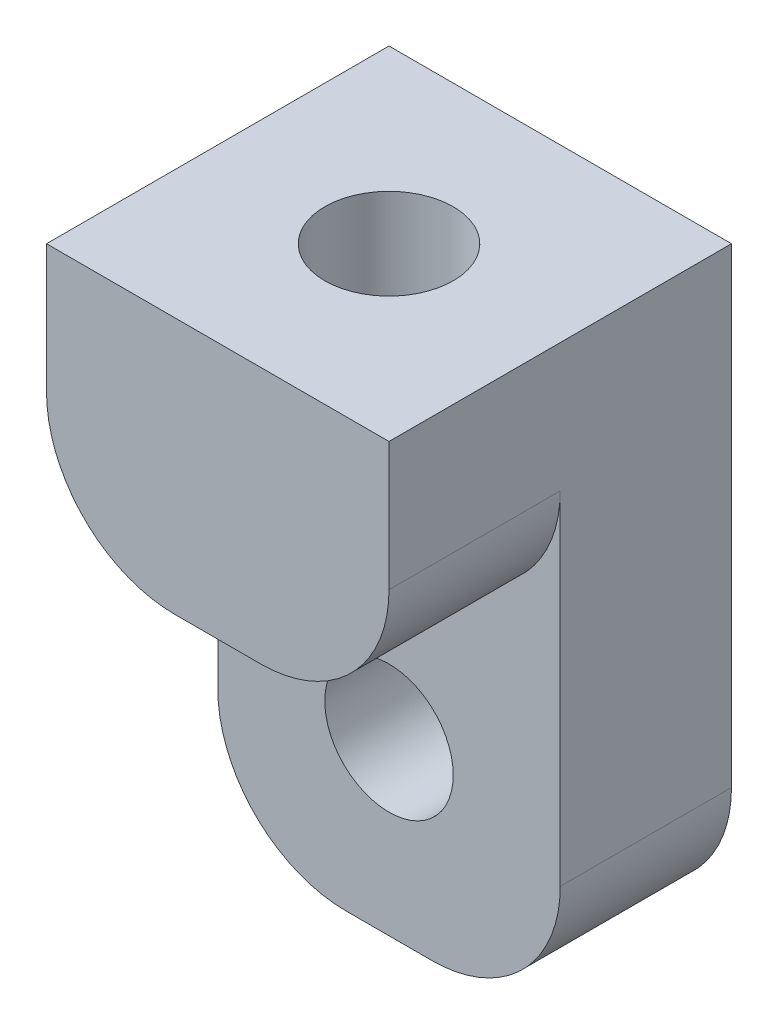
SolidWorks part; units mm, degrees
material "ABS"
ref_plane "Front Plane" through (0, 0, 0) normal (0, 0, 1) x (1, 0, 0)
ref_plane "Top Plane" through (0, 0, 0) normal (0, 1, 0) x (1, 0, 0)
ref_plane "Right Plane" through (0, 0, 0) normal (1, 0, 0) x (0, 0, -1)
sketch "Sketch1" plane through (0, 0, 0) normal (0, 0, 1) x (1, 0, 0)
  line L1 (-20, 50) -> (20, 50)
  line L2 (-20, 50) -> (-20, -20)
  line L3 (-20, -20) -> (20, -20)
  line L4 (20, 50) -> (20, -20)
  circle A0 centre (0, 0) radius 7.5
  point P6 (0, 0)
  point P8 (30.9278, -35.0258)
  point P9 (0, -20)
  point P10 (-25.8247, 54.201)
  dimension "D1" = 15
  dimension "D2" = 20
  dimension "D3" = 70
  dimension "D4" = 40
extrude "Boss-Extrude1" add sketch "Sketch1" along normal blind 40 contours L2 L3 L4 L1
sketch "Sketch2" plane through (0, 50, 0) normal (0, 1, 0) x (1, 0, 0)
  line L0 (-20, 0) -> (20, -40) construction
  line L4 (20, 0) -> (-20, 0)
  line L5 (-20, 0) -> (-20, -40)
  line L6 (-20, -40) -> (20, -40)
  line L7 (20, -40) -> (20, 0)
  line L8 (20, 0) -> (-20, 0)
  line L9 (-20, 0) -> (-20, -40)
  line L10 (-20, -40) -> (20, -40)
  line L11 (20, -40) -> (20, 0)
  circle A0 centre (0, -20) radius 7.5
  point P6 (0, -20)
  dimension "D2" = 15
  dimension "D1" = 0
extrude "Cut-Extrude1" cut sketch "Sketch2" against normal blind 20 contours L0 A0 | A0 L0
sketch "Sketch3" plane through (0, 0, 40) normal (0, 0, 1) x (1, 0, 0)
  line L0 (20, -20) -> (20, 50) construction
  line L1 (-20, -20) -> (20, -20)
  line L2 (-20, -20) -> (-20, 20)
  line L3 (-20, 20) -> (20, 20)
  line L4 (20, -20) -> (20, 20)
  dimension "D1" = 40
extrude "Cut-Extrude2" cut sketch "Sketch3" against normal blind 20 contours L2 L3 L4 L1
fillet "Fillet1" radius 15 4 edges at (-20, 20, 30) (20, 20, 30) (20, -20, 10) (-20, -20, 10)
